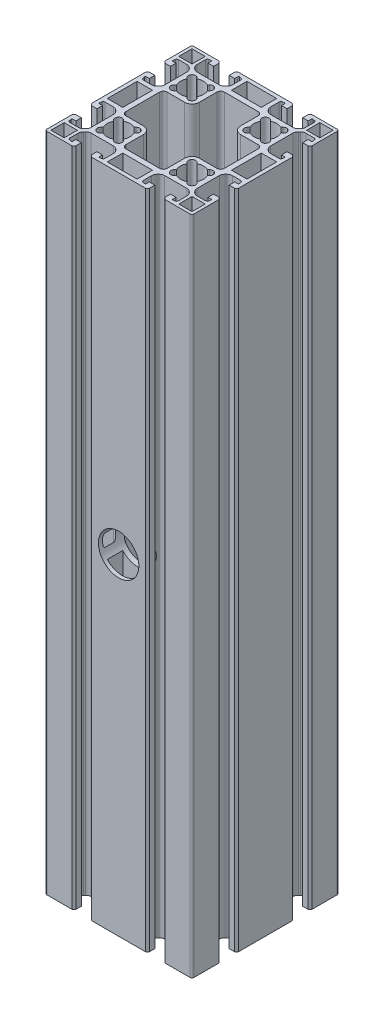
SolidWorks part; units mm, degrees
ref_plane "Front Plane" through (0, 0, 0) normal (0, 0, 1) x (1, 0, 0)
ref_plane "Top Plane" through (0, 0, 0) normal (0, 1, 0) x (1, 0, 0)
ref_plane "Right Plane" through (0, 0, 0) normal (1, 0, 0) x (0, 0, -1)
sketch "Sketch1" plane through (0, 0, 0) normal (0, 1, 0) x (1, 0, 0)
  line L0 (16.5224, 10.1082) -> (17.1083, 10.6941)
  line L2 (14.2799, 13.5226) -> (13.694, 12.9366)
  line L7 (13.694, 19.6541) -> (14.2799, 19.0682)
  line L8 (17.1083, 21.8966) -> (16.5224, 22.4826)
  line L9 (23.2399, 22.4826) -> (22.654, 21.8966)
  line L10 (25.4824, 19.0682) -> (26.0683, 19.6541)
  line L11 (26.0683, 12.9366) -> (25.4824, 13.5226)
  line L12 (22.654, 10.6941) -> (23.2399, 10.1082)
  line L13 (-29.7188, -11.8046) -> (-29.7188, 4.3954)
  line L14 (-38.1188, -11.8046) -> (-29.7188, -11.8046)
  line L15 (-38.1188, 4.3954) -> (-38.1188, -11.8046)
  line L16 (-29.7188, 4.3954) -> (-38.1188, 4.3954)
  line L17 (-23.4776, 10.1082) -> (-22.8917, 10.6941)
  line L18 (-25.7201, 13.5226) -> (-26.306, 12.9366)
  line L19 (-26.306, 19.6541) -> (-25.7201, 19.0682)
  line L20 (-22.8917, 21.8966) -> (-23.4776, 22.4826)
  line L21 (-16.7601, 22.4826) -> (-17.346, 21.8966)
  line L22 (-14.5176, 19.0682) -> (-13.9317, 19.6541)
  line L23 (-13.9317, 12.9366) -> (-14.5176, 13.5226)
  line L24 (-17.346, 10.6941) -> (-16.7601, 10.1082)
  line L26 (23.2399, -17.5174) -> (22.654, -18.1034)
  line L27 (25.4824, -20.9318) -> (26.0683, -20.3459)
  line L28 (26.0683, -27.0634) -> (25.4824, -26.4774)
  line L29 (22.654, -29.3059) -> (23.2399, -29.8918)
  line L30 (16.5224, -29.8918) -> (17.1083, -29.3059)
  line L31 (14.2799, -26.4774) -> (13.694, -27.0634)
  line L32 (13.694, -20.3459) -> (14.2799, -20.9318)
  line L33 (17.1083, -18.1034) -> (16.5224, -17.5174)
  line L41 (-31.3188, -34.9046) -> (-38.5188, -34.9046)
  line L42 (-31.3188, -42.1046) -> (-31.3188, -34.9046)
  line L43 (-38.5188, -42.1046) -> (-31.3188, -42.1046)
  line L44 (-38.5188, -34.9046) -> (-38.5188, -42.1046)
  line L45 (-16.7601, -17.5174) -> (-17.346, -18.1034)
  line L46 (-14.5176, -20.9318) -> (-13.9317, -20.3459)
  line L51 (-13.9317, -27.0634) -> (-14.5176, -26.4774)
  line L52 (-17.346, -29.3059) -> (-16.7601, -29.8918)
  line L53 (-23.4776, -29.8918) -> (-22.8917, -29.3059)
  line L54 (-25.7201, -26.4774) -> (-26.306, -27.0634)
  line L55 (-26.306, -20.3459) -> (-25.7201, -20.9318)
  line L56 (-22.8917, -18.1034) -> (-23.4776, -17.5174)
  line L57 (-38.5188, 27.4954) -> (-31.3188, 27.4954)
  line L58 (-38.5188, 34.6954) -> (-38.5188, 27.4954)
  line L59 (-31.3188, 34.6954) -> (-38.5188, 34.6954)
  line L60 (-31.3188, 27.4954) -> (-31.3188, 34.6954)
  line L61 (38.2812, -34.9046) -> (31.0812, -34.9046)
  line L62 (38.2812, -42.1046) -> (38.2812, -34.9046)
  line L63 (31.0812, -42.1046) -> (38.2812, -42.1046)
  line L64 (31.0812, -34.9046) -> (31.0812, -42.1046)
  line L65 (31.0812, 27.4954) -> (38.2812, 27.4954)
  line L66 (31.0812, 34.6954) -> (31.0812, 27.4954)
  line L67 (38.2812, 34.6954) -> (31.0812, 34.6954)
  line L68 (38.2812, 27.4954) -> (38.2812, 34.6954)
  line L69 (-8.2188, 34.2954) -> (-8.2188, 25.8954)
  line L70 (7.9812, 34.2954) -> (-8.2188, 34.2954)
  line L71 (7.9812, 25.8954) -> (7.9812, 34.2954)
  line L72 (-8.2188, 25.8954) -> (7.9812, 25.8954)
  line L79 (11.0812, -28.5046) -> (11.0812, -18.9046)
  line L80 (-9.3188, -30.5046) -> (9.0812, -30.5046)
  line L81 (-11.3188, -18.9046) -> (-11.3188, -28.5046)
  line L82 (-24.9188, -14.9046) -> (-15.3188, -14.9046)
  line L83 (-26.9188, 5.4954) -> (-26.9188, -12.9046)
  line L84 (-15.3188, 7.4954) -> (-24.9188, 7.4954)
  line L89 (-11.3188, 21.0954) -> (-11.3188, 11.4954)
  line L90 (9.0812, 23.0954) -> (-9.3188, 23.0954)
  line L91 (11.0812, 11.4954) -> (11.0812, 21.0954)
  line L92 (24.6812, 7.4954) -> (15.0812, 7.4954)
  line L93 (26.6812, -12.9046) -> (26.6812, 5.4954)
  line L94 (15.0812, -14.9046) -> (24.6812, -14.9046)
  line L95 (7.9812, -33.3046) -> (-8.2188, -33.3046)
  line L96 (7.9812, -41.7046) -> (7.9812, -33.3046)
  line L97 (-8.2188, -41.7046) -> (7.9812, -41.7046)
  line L98 (-8.2188, -33.3046) -> (-8.2188, -41.7046)
  line L99 (29.4812, 4.3954) -> (29.4812, -11.8046)
  line L100 (37.8812, 4.3954) -> (29.4812, 4.3954)
  line L101 (37.8812, -11.8046) -> (37.8812, 4.3954)
  line L102 (29.4812, -11.8046) -> (37.8812, -11.8046)
  line L103 (39.8812, -42.7046) -> (39.8812, -28.9546)
  line L104 (39.8812, -28.9546) -> (38.8812, -27.9546)
  line L105 (38.8812, -27.9546) -> (35.8812, -27.9546)
  line L106 (35.8812, -27.9546) -> (35.8812, -30.9546)
  line L107 (35.8812, -30.9546) -> (37.4853, -30.9546)
  line L108 (37.9777, -31.5414) -> (37.7979, -32.5609)
  line L109 (36.9116, -33.3046) -> (32.215, -33.3046)
  line L110 (30.0937, -32.4259) -> (29.5598, -31.8921)
  line L111 (28.6812, -29.7708) -> (28.6812, -17.6385)
  line L118 (29.5598, -15.5172) -> (30.0937, -14.9833)
  line L119 (32.215, -14.1046) -> (36.9116, -14.1046)
  line L120 (37.7979, -14.8483) -> (37.9777, -15.8678)
  line L121 (37.4853, -16.4546) -> (35.8812, -16.4546)
  line L122 (35.8812, -16.4546) -> (35.8812, -19.4546)
  line L123 (35.8812, -19.4546) -> (38.8812, -19.4546)
  line L128 (38.8812, -19.4546) -> (39.8812, -18.4546)
  line L129 (39.8812, -18.4546) -> (39.8812, 11.0454)
  line L130 (39.8812, 11.0454) -> (38.8812, 12.0454)
  line L131 (38.8812, 12.0454) -> (35.8812, 12.0454)
  line L132 (35.8812, 12.0454) -> (35.8812, 9.0454)
  line L133 (35.8812, 9.0454) -> (37.4853, 9.0454)
  line L134 (37.9777, 8.4586) -> (37.7979, 7.4391)
  line L135 (36.9116, 6.6954) -> (32.215, 6.6954)
  line L136 (30.0937, 7.5741) -> (29.5598, 8.1079)
  line L137 (28.6812, 10.2292) -> (28.6812, 22.3615)
  line L138 (29.5598, 24.4828) -> (30.0937, 25.0167)
  line L139 (32.215, 25.8954) -> (36.9116, 25.8954)
  line L140 (37.7979, 25.1517) -> (37.9777, 24.1322)
  line L141 (37.4853, 23.5454) -> (35.8812, 23.5454)
  line L142 (35.8812, 23.5454) -> (35.8812, 20.5454)
  line L143 (35.8812, 20.5454) -> (38.8812, 20.5454)
  line L144 (38.8812, 20.5454) -> (39.8812, 21.5454)
  line L145 (39.8812, 21.5454) -> (39.8812, 35.2954)
  line L146 (38.8812, 36.2954) -> (25.1312, 36.2954)
  line L147 (25.1312, 36.2954) -> (24.1312, 35.2954)
  line L148 (24.1312, 35.2954) -> (24.1312, 32.2954)
  line L149 (24.1312, 32.2954) -> (27.1312, 32.2954)
  line L150 (27.1312, 32.2954) -> (27.1312, 33.8995)
  line L157 (27.718, 34.3919) -> (28.7374, 34.2122)
  line L158 (29.4812, 33.3258) -> (29.4812, 28.6292)
  line L159 (28.6025, 26.5079) -> (28.0686, 25.9741)
  line L160 (25.9473, 25.0954) -> (13.815, 25.0954)
  line L161 (11.6937, 25.9741) -> (11.1598, 26.5079)
  line L162 (10.2812, 28.6292) -> (10.2812, 33.3258)
  line L167 (11.0249, 34.2122) -> (12.0443, 34.3919)
  line L172 (12.6312, 33.8995) -> (12.6312, 32.2954)
  line L173 (12.6312, 32.2954) -> (15.6312, 32.2954)
  line L178 (15.6312, 32.2954) -> (15.6312, 35.2954)
  line L179 (15.6312, 35.2954) -> (14.6312, 36.2954)
  line L183 (14.6312, 36.2954) -> (-14.8688, 36.2954)
  line L184 (-14.8688, 36.2954) -> (-15.8688, 35.2954)
  line L189 (-15.8688, 35.2954) -> (-15.8688, 32.2954)
  line L190 (-15.8688, 32.2954) -> (-12.8688, 32.2954)
  line L195 (-12.8688, 32.2954) -> (-12.8688, 33.8995)
  line L196 (-12.282, 34.3919) -> (-11.2626, 34.2122)
  line L198 (-10.5188, 33.3258) -> (-10.5188, 28.6292)
  line L199 (-11.3975, 26.5079) -> (-11.9314, 25.9741)
  line L200 (-14.0527, 25.0954) -> (-26.185, 25.0954)
  line L201 (-28.3063, 25.9741) -> (-28.8402, 26.5079)
  line L202 (-29.7188, 28.6292) -> (-29.7188, 33.3258)
  line L203 (-28.9751, 34.2122) -> (-27.9557, 34.3919)
  line L204 (-27.3688, 33.8995) -> (-27.3688, 32.2954)
  line L205 (-27.3688, 32.2954) -> (-24.3688, 32.2954)
  line L206 (-24.3688, 32.2954) -> (-24.3688, 35.2954)
  line L207 (-24.3688, 35.2954) -> (-25.3688, 36.2954)
  line L208 (-25.3688, 36.2954) -> (-39.1188, 36.2954)
  line L209 (-40.1188, 35.2954) -> (-40.1188, 21.5454)
  line L210 (-40.1188, 21.5454) -> (-39.1188, 20.5454)
  line L211 (-39.1188, 20.5454) -> (-36.1188, 20.5454)
  line L212 (-36.1188, 20.5454) -> (-36.1188, 23.5454)
  line L213 (-36.1188, 23.5454) -> (-37.723, 23.5454)
  line L214 (-38.2154, 24.1322) -> (-38.0356, 25.1517)
  line L215 (-37.1493, 25.8954) -> (-32.4527, 25.8954)
  line L216 (-30.3314, 25.0167) -> (-29.7975, 24.4828)
  line L217 (-28.9188, 22.3615) -> (-28.9188, 10.2292)
  line L218 (-29.7975, 8.1079) -> (-30.3314, 7.5741)
  line L219 (-32.4527, 6.6954) -> (-37.1493, 6.6954)
  line L220 (-38.0356, 7.4391) -> (-38.2154, 8.4586)
  line L221 (-37.723, 9.0454) -> (-36.1188, 9.0454)
  line L222 (-36.1188, 9.0454) -> (-36.1188, 12.0454)
  line L223 (-36.1188, 12.0454) -> (-39.1188, 12.0454)
  line L224 (-39.1188, 12.0454) -> (-40.1188, 11.0454)
  line L225 (-40.1188, 11.0454) -> (-40.1188, -18.4546)
  line L226 (-40.1188, -18.4546) -> (-39.1188, -19.4546)
  line L227 (-39.1188, -19.4546) -> (-36.1188, -19.4546)
  line L228 (-36.1188, -19.4546) -> (-36.1188, -16.4546)
  line L229 (-36.1188, -16.4546) -> (-37.723, -16.4546)
  line L230 (-38.2154, -15.8678) -> (-38.0356, -14.8483)
  line L231 (-37.1493, -14.1046) -> (-32.4527, -14.1046)
  line L232 (-30.3314, -14.9833) -> (-29.7975, -15.5172)
  line L233 (-28.9188, -17.6385) -> (-28.9188, -29.7708)
  line L234 (-29.7975, -31.8921) -> (-30.3314, -32.4259)
  line L235 (-32.4527, -33.3046) -> (-37.1493, -33.3046)
  line L236 (-38.0356, -32.5609) -> (-38.2154, -31.5414)
  line L237 (-37.723, -30.9546) -> (-36.1188, -30.9546)
  line L238 (-36.1188, -30.9546) -> (-36.1188, -27.9546)
  line L239 (-36.1188, -27.9546) -> (-39.1188, -27.9546)
  line L240 (-39.1188, -27.9546) -> (-40.1188, -28.9546)
  line L241 (-40.1188, -28.9546) -> (-40.1188, -42.7046)
  line L242 (-39.1188, -43.7046) -> (-25.3688, -43.7046)
  line L243 (-25.3688, -43.7046) -> (-24.3688, -42.7046)
  line L244 (-24.3688, -42.7046) -> (-24.3688, -39.7046)
  line L245 (-24.3688, -39.7046) -> (-27.3688, -39.7046)
  line L246 (-27.3688, -39.7046) -> (-27.3688, -41.3087)
  line L247 (-27.9557, -41.8011) -> (-28.9751, -41.6214)
  line L248 (-29.7188, -40.7351) -> (-29.7188, -36.0385)
  line L249 (-28.8402, -33.9172) -> (-28.3063, -33.3833)
  line L250 (-26.185, -32.5046) -> (-14.0527, -32.5046)
  line L251 (-11.9314, -33.3833) -> (-11.3975, -33.9172)
  line L252 (-10.5188, -36.0385) -> (-10.5188, -40.7351)
  line L253 (-11.2626, -41.6214) -> (-12.282, -41.8011)
  line L254 (-12.8688, -41.3087) -> (-12.8688, -39.7046)
  line L255 (-12.8688, -39.7046) -> (-15.8688, -39.7046)
  line L256 (-15.8688, -39.7046) -> (-15.8688, -42.7046)
  line L257 (-15.8688, -42.7046) -> (-14.8688, -43.7046)
  line L258 (-14.8688, -43.7046) -> (14.6312, -43.7046)
  line L259 (14.6312, -43.7046) -> (15.6312, -42.7046)
  line L260 (15.6312, -42.7046) -> (15.6312, -39.7046)
  line L261 (15.6312, -39.7046) -> (12.6312, -39.7046)
  line L262 (12.6312, -39.7046) -> (12.6312, -41.3087)
  line L263 (12.0443, -41.8011) -> (11.0249, -41.6214)
  line L264 (10.2812, -40.7351) -> (10.2812, -36.0385)
  line L265 (11.1598, -33.9172) -> (11.6937, -33.3833)
  line L266 (13.815, -32.5046) -> (25.9473, -32.5046)
  line L267 (28.0686, -33.3833) -> (28.6025, -33.9172)
  line L268 (29.4812, -36.0385) -> (29.4812, -40.7351)
  line L269 (28.7374, -41.6214) -> (27.718, -41.8011)
  line L270 (27.1312, -41.3087) -> (27.1312, -39.7046)
  line L271 (27.1312, -39.7046) -> (24.1312, -39.7046)
  line L272 (24.1312, -39.7046) -> (24.1312, -42.7046)
  line L273 (24.1312, -42.7046) -> (25.1312, -43.7046)
  line L274 (25.1312, -43.7046) -> (38.8812, -43.7046)
  arc A0 (17.1083, 10.6941) -> (22.654, 10.6941) centre (19.8812, 16.2954) ccw
  arc A1 (13.694, 12.9366) -> (16.5224, 10.1082) centre (15.1082, 11.5224) ccw
  arc A2 (14.2799, 19.0682) -> (14.2799, 13.5226) centre (19.8812, 16.2954) ccw
  arc A3 (16.5224, 22.4826) -> (13.694, 19.6541) centre (15.1082, 21.0684) ccw
  arc A4 (22.654, 21.8966) -> (17.1083, 21.8966) centre (19.8812, 16.2954) ccw
  arc A5 (26.0683, 19.6541) -> (23.2399, 22.4826) centre (24.6541, 21.0684) ccw
  arc A6 (25.4824, 13.5226) -> (25.4824, 19.0682) centre (19.8812, 16.2954) ccw
  arc A7 (23.2399, 10.1082) -> (26.0683, 12.9366) centre (24.6541, 11.5224) ccw
  arc A8 (-22.8917, 10.6941) -> (-17.346, 10.6941) centre (-20.1188, 16.2954) ccw
  arc A9 (-26.306, 12.9366) -> (-23.4776, 10.1082) centre (-24.8918, 11.5224) ccw
  arc A10 (-25.7201, 19.0682) -> (-25.7201, 13.5226) centre (-20.1188, 16.2954) ccw
  arc A11 (-23.4776, 22.4826) -> (-26.306, 19.6541) centre (-24.8918, 21.0684) ccw
  arc A12 (-17.346, 21.8966) -> (-22.8917, 21.8966) centre (-20.1188, 16.2954) ccw
  arc A13 (-13.9317, 19.6541) -> (-16.7601, 22.4826) centre (-15.3459, 21.0684) ccw
  arc A14 (-14.5176, 13.5226) -> (-14.5176, 19.0682) centre (-20.1188, 16.2954) ccw
  arc A15 (-16.7601, 10.1082) -> (-13.9317, 12.9366) centre (-15.3459, 11.5224) ccw
  arc A50 (22.654, -18.1034) -> (17.1083, -18.1034) centre (19.8812, -23.7046) ccw
  arc A51 (26.0683, -20.3459) -> (23.2399, -17.5174) centre (24.6541, -18.9316) ccw
  arc A52 (25.4824, -26.4774) -> (25.4824, -20.9318) centre (19.8812, -23.7046) ccw
  arc A53 (23.2399, -29.8918) -> (26.0683, -27.0634) centre (24.6541, -28.4776) ccw
  arc A54 (17.1083, -29.3059) -> (22.654, -29.3059) centre (19.8812, -23.7046) ccw
  arc A55 (13.694, -27.0634) -> (16.5224, -29.8918) centre (15.1082, -28.4776) ccw
  arc A56 (14.2799, -20.9318) -> (14.2799, -26.4774) centre (19.8812, -23.7046) ccw
  arc A57 (16.5224, -17.5174) -> (13.694, -20.3459) centre (15.1082, -18.9316) ccw
  arc A58 (-17.346, -18.1034) -> (-22.8917, -18.1034) centre (-20.1188, -23.7046) ccw
  arc A59 (-13.9317, -20.3459) -> (-16.7601, -17.5174) centre (-15.3459, -18.9316) ccw
  arc A60 (-14.5176, -26.4774) -> (-14.5176, -20.9318) centre (-20.1188, -23.7046) ccw
  arc A61 (-16.7601, -29.8918) -> (-13.9317, -27.0634) centre (-15.3459, -28.4776) ccw
  arc A62 (-22.8917, -29.3059) -> (-17.346, -29.3059) centre (-20.1188, -23.7046) ccw
  arc A63 (-26.306, -27.0634) -> (-23.4776, -29.8918) centre (-24.8918, -28.4776) ccw
  arc A64 (-25.7201, -20.9318) -> (-25.7201, -26.4774) centre (-20.1188, -23.7046) ccw
  arc A65 (-23.4776, -17.5174) -> (-26.306, -20.3459) centre (-24.8918, -18.9316) ccw
  arc A66 (15.0812, -14.9046) -> (11.0812, -18.9046) centre (15.0812, -18.9046) ccw
  arc A67 (9.0812, -30.5046) -> (11.0812, -28.5046) centre (9.0812, -28.5046) ccw
  arc A68 (-11.3188, -28.5046) -> (-9.3188, -30.5046) centre (-9.3188, -28.5046) ccw
  arc A69 (-11.3188, -18.9046) -> (-15.3188, -14.9046) centre (-15.3188, -18.9046) ccw
  arc A70 (-26.9188, -12.9046) -> (-24.9188, -14.9046) centre (-24.9188, -12.9046) ccw
  arc A71 (-24.9188, 7.4954) -> (-26.9188, 5.4954) centre (-24.9188, 5.4954) ccw
  arc A72 (-15.3188, 7.4954) -> (-11.3188, 11.4954) centre (-15.3188, 11.4954) ccw
  arc A73 (-9.3188, 23.0954) -> (-11.3188, 21.0954) centre (-9.3188, 21.0954) ccw
  arc A74 (11.0812, 21.0954) -> (9.0812, 23.0954) centre (9.0812, 21.0954) ccw
  arc A75 (11.0812, 11.4954) -> (15.0812, 7.4954) centre (15.0812, 11.4954) ccw
  arc A76 (26.6812, 5.4954) -> (24.6812, 7.4954) centre (24.6812, 5.4954) ccw
  arc A77 (24.6812, -14.9046) -> (26.6812, -12.9046) centre (24.6812, -12.9046) ccw
  arc A78 (38.8812, -43.7046) -> (39.8812, -42.7046) centre (38.8812, -42.7046) ccw
  arc A79 (37.9777, -31.5414) -> (37.4853, -30.9546) centre (37.4853, -31.4546) ccw
  arc A80 (36.9116, -33.3046) -> (37.7979, -32.5609) centre (36.9116, -32.4046) ccw
  arc A81 (30.0937, -32.4259) -> (32.215, -33.3046) centre (32.215, -30.3046) ccw
  arc A82 (28.6812, -29.7708) -> (29.5598, -31.8921) centre (31.6812, -29.7708) ccw
  arc A83 (29.5598, -15.5172) -> (28.6812, -17.6385) centre (31.6812, -17.6385) ccw
  arc A84 (32.215, -14.1046) -> (30.0937, -14.9833) centre (32.215, -17.1046) ccw
  arc A85 (37.7979, -14.8483) -> (36.9116, -14.1046) centre (36.9116, -15.0046) ccw
  arc A86 (37.4853, -16.4546) -> (37.9777, -15.8678) centre (37.4853, -15.9546) ccw
  arc A87 (37.9777, 8.4586) -> (37.4853, 9.0454) centre (37.4853, 8.5454) ccw
  arc A88 (36.9116, 6.6954) -> (37.7979, 7.4391) centre (36.9116, 7.5954) ccw
  arc A89 (30.0937, 7.5741) -> (32.215, 6.6954) centre (32.215, 9.6954) ccw
  arc A90 (28.6812, 10.2292) -> (29.5598, 8.1079) centre (31.6812, 10.2292) ccw
  arc A91 (29.5598, 24.4828) -> (28.6812, 22.3615) centre (31.6812, 22.3615) ccw
  arc A92 (32.215, 25.8954) -> (30.0937, 25.0167) centre (32.215, 22.8954) ccw
  arc A93 (37.7979, 25.1517) -> (36.9116, 25.8954) centre (36.9116, 24.9954) ccw
  arc A94 (37.4853, 23.5454) -> (37.9777, 24.1322) centre (37.4853, 24.0454) ccw
  arc A95 (39.8812, 35.2954) -> (38.8812, 36.2954) centre (38.8812, 35.2954) ccw
  arc A96 (27.718, 34.3919) -> (27.1312, 33.8995) centre (27.6312, 33.8995) ccw
  arc A97 (29.4812, 33.3258) -> (28.7374, 34.2122) centre (28.5812, 33.3258) ccw
  arc A98 (28.6025, 26.5079) -> (29.4812, 28.6292) centre (26.4812, 28.6292) ccw
  arc A99 (25.9473, 25.0954) -> (28.0686, 25.9741) centre (25.9473, 28.0954) ccw
  arc A100 (11.6937, 25.9741) -> (13.815, 25.0954) centre (13.815, 28.0954) ccw
  arc A101 (10.2812, 28.6292) -> (11.1598, 26.5079) centre (13.2812, 28.6292) ccw
  arc A102 (11.0249, 34.2122) -> (10.2812, 33.3258) centre (11.1812, 33.3258) ccw
  arc A103 (12.6312, 33.8995) -> (12.0443, 34.3919) centre (12.1312, 33.8995) ccw
  arc A104 (-12.282, 34.3919) -> (-12.8688, 33.8995) centre (-12.3688, 33.8995) ccw
  arc A105 (-10.5188, 33.3258) -> (-11.2626, 34.2122) centre (-11.4188, 33.3258) ccw
  arc A106 (-11.3975, 26.5079) -> (-10.5188, 28.6292) centre (-13.5188, 28.6292) ccw
  arc A107 (-14.0527, 25.0954) -> (-11.9314, 25.9741) centre (-14.0527, 28.0954) ccw
  arc A108 (-28.3063, 25.9741) -> (-26.185, 25.0954) centre (-26.185, 28.0954) ccw
  arc A109 (-29.7188, 28.6292) -> (-28.8402, 26.5079) centre (-26.7188, 28.6292) ccw
  arc A110 (-28.9751, 34.2122) -> (-29.7188, 33.3258) centre (-28.8188, 33.3258) ccw
  arc A111 (-27.3688, 33.8995) -> (-27.9557, 34.3919) centre (-27.8688, 33.8995) ccw
  arc A112 (-39.1188, 36.2954) -> (-40.1188, 35.2954) centre (-39.1188, 35.2954) ccw
  arc A113 (-38.2154, 24.1322) -> (-37.723, 23.5454) centre (-37.723, 24.0454) ccw
  arc A114 (-37.1493, 25.8954) -> (-38.0356, 25.1517) centre (-37.1493, 24.9954) ccw
  arc A115 (-30.3314, 25.0167) -> (-32.4527, 25.8954) centre (-32.4527, 22.8954) ccw
  arc A116 (-28.9188, 22.3615) -> (-29.7975, 24.4828) centre (-31.9188, 22.3615) ccw
  arc A117 (-29.7975, 8.1079) -> (-28.9188, 10.2292) centre (-31.9188, 10.2292) ccw
  arc A118 (-32.4527, 6.6954) -> (-30.3314, 7.5741) centre (-32.4527, 9.6954) ccw
  arc A119 (-38.0356, 7.4391) -> (-37.1493, 6.6954) centre (-37.1493, 7.5954) ccw
  arc A120 (-37.723, 9.0454) -> (-38.2154, 8.4586) centre (-37.723, 8.5454) ccw
  arc A121 (-38.2154, -15.8678) -> (-37.723, -16.4546) centre (-37.723, -15.9546) ccw
  arc A122 (-37.1493, -14.1046) -> (-38.0356, -14.8483) centre (-37.1493, -15.0046) ccw
  arc A123 (-30.3314, -14.9833) -> (-32.4527, -14.1046) centre (-32.4527, -17.1046) ccw
  arc A124 (-28.9188, -17.6385) -> (-29.7975, -15.5172) centre (-31.9188, -17.6385) ccw
  arc A125 (-29.7975, -31.8921) -> (-28.9188, -29.7708) centre (-31.9188, -29.7708) ccw
  arc A126 (-32.4527, -33.3046) -> (-30.3314, -32.4259) centre (-32.4527, -30.3046) ccw
  arc A127 (-38.0356, -32.5609) -> (-37.1493, -33.3046) centre (-37.1493, -32.4046) ccw
  arc A128 (-37.723, -30.9546) -> (-38.2154, -31.5414) centre (-37.723, -31.4546) ccw
  arc A129 (-40.1188, -42.7046) -> (-39.1188, -43.7046) centre (-39.1188, -42.7046) ccw
  arc A130 (-27.9557, -41.8011) -> (-27.3688, -41.3087) centre (-27.8688, -41.3087) ccw
  arc A131 (-29.7188, -40.7351) -> (-28.9751, -41.6214) centre (-28.8188, -40.7351) ccw
  arc A132 (-28.8402, -33.9172) -> (-29.7188, -36.0385) centre (-26.7188, -36.0385) ccw
  arc A133 (-26.185, -32.5046) -> (-28.3063, -33.3833) centre (-26.185, -35.5046) ccw
  arc A134 (-11.9314, -33.3833) -> (-14.0527, -32.5046) centre (-14.0527, -35.5046) ccw
  arc A135 (-10.5188, -36.0385) -> (-11.3975, -33.9172) centre (-13.5188, -36.0385) ccw
  arc A136 (-11.2626, -41.6214) -> (-10.5188, -40.7351) centre (-11.4188, -40.7351) ccw
  arc A137 (-12.8688, -41.3087) -> (-12.282, -41.8011) centre (-12.3688, -41.3087) ccw
  arc A138 (12.0443, -41.8011) -> (12.6312, -41.3087) centre (12.1312, -41.3087) ccw
  arc A139 (10.2812, -40.7351) -> (11.0249, -41.6214) centre (11.1812, -40.7351) ccw
  arc A140 (11.1598, -33.9172) -> (10.2812, -36.0385) centre (13.2812, -36.0385) ccw
  arc A141 (13.815, -32.5046) -> (11.6937, -33.3833) centre (13.815, -35.5046) ccw
  arc A142 (28.0686, -33.3833) -> (25.9473, -32.5046) centre (25.9473, -35.5046) ccw
  arc A143 (29.4812, -36.0385) -> (28.6025, -33.9172) centre (26.4812, -36.0385) ccw
  arc A144 (28.7374, -41.6214) -> (29.4812, -40.7351) centre (28.5812, -40.7351) ccw
  arc A145 (27.1312, -41.3087) -> (27.718, -41.8011) centre (27.6312, -41.3087) ccw
extrude "Boss-Extrude1" add sketch "Sketch1" along normal blind 360
sketch "Sketch3" plane through (0, 0, -36.2954) normal (0, 0, -1) x (-1, 0, 0)
  line L0 (0.1188, 360) -> (0, 0) construction
  line L1 (-14.6312, 360) -> (14.8688, 360) construction
  circle A0 centre (0.0594, 180) radius 11
extrude "Cut-Extrude1" cut sketch "Sketch3" against normal through all
